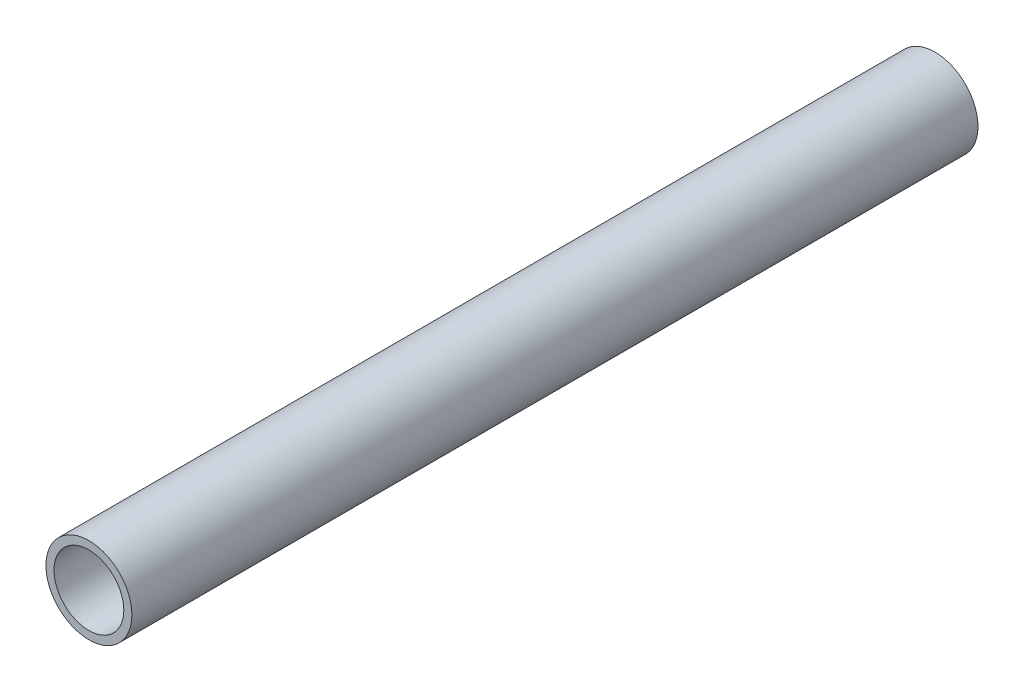
SolidWorks part; units mm, degrees
ref_plane "Alzado" through (0, 0, 0) normal (0, 0, 1) x (1, 0, 0)
ref_plane "Planta" through (0, 0, 0) normal (0, 1, 0) x (1, 0, 0)
ref_plane "Vista lateral" through (0, 0, 0) normal (1, 0, 0) x (0, 0, -1)
sketch "Croquis1" plane through (0, 0, 0) normal (0, 0, 1) x (1, 0, 0)
  circle A0 centre (0, 0) radius 16
  dimension "D1" = 32
extrude "Extruir1" add sketch "Croquis1" along normal mid plane 315
shell "Vaciado1" thickness 3
